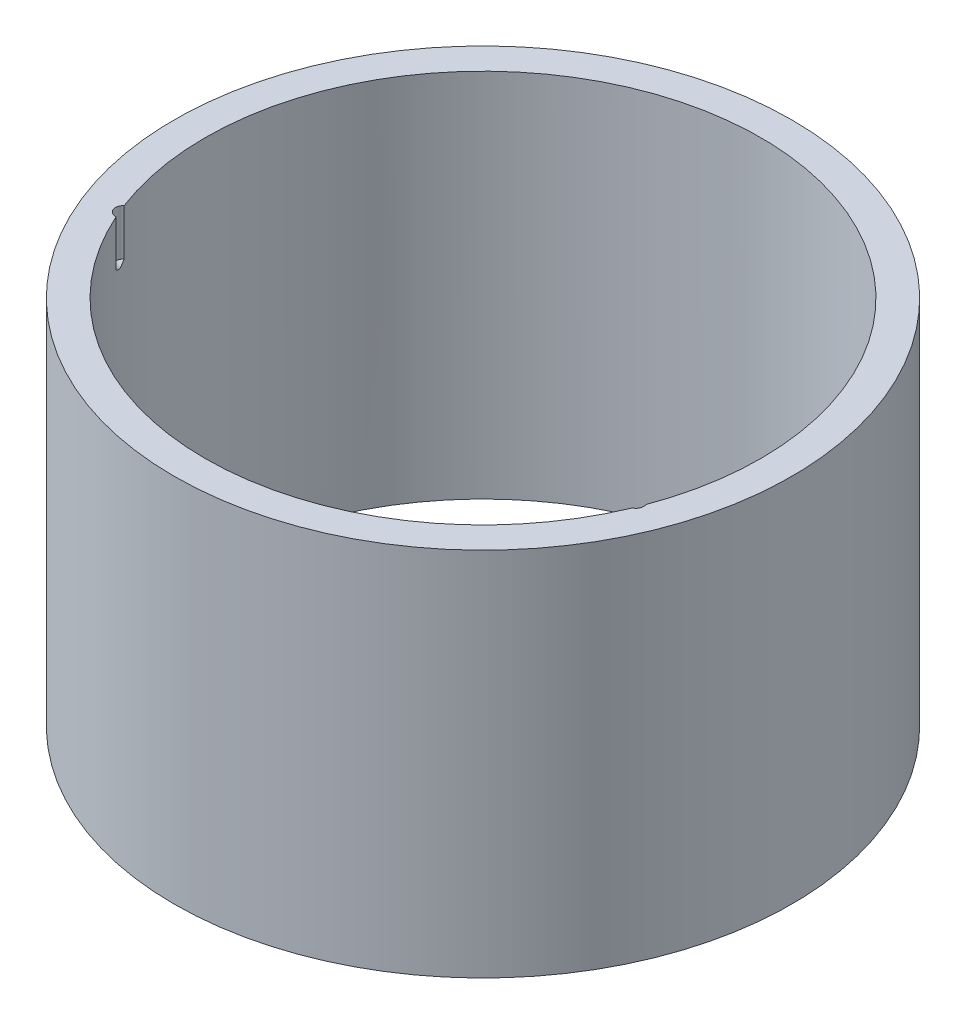
SolidWorks part; units mm, degrees
ref_plane "Front Plane" through (0, 0, 0) normal (0, 0, 1) x (1, 0, 0)
ref_plane "Top Plane" through (0, 0, 0) normal (0, 1, 0) x (1, 0, 0)
ref_plane "Right Plane" through (0, 0, 0) normal (1, 0, 0) x (0, 0, -1)
sketch "Sketch1" plane through (0, 0, 0) normal (0, 1, 0) x (1, 0, 0)
  circle A0 centre (0, 0) radius 50
  dimension "D1" = 100
extrude "Boss-Extrude1" add sketch "Sketch1" along normal blind 60 contours A0
sketch "Sketch2" plane through (0, 60, 0) normal (0, 1, 0) x (1, 0, 0)
  circle A0 centre (0, 0) radius 45
  dimension "D1" = 90
extrude "Cut-Extrude1" cut sketch "Sketch2" against normal through all
hole_wizard "M3 Tapped Hole2" positions "Sketch5" profile "Sketch6" tap size "M3" standard "ISO"
sketch "Sketch5" plane through (-125, 60, -260) normal (0, 1, 0) x (-1, 0, 0)
  point P0 (-125.5887, 346.3435)
  point P1 (-83.7893, 277.0519)
  point P2 (-165.9855, 276.2103)
  point P3 (165.6896, 275.8726)
  point P4 (83.5295, 276.2529)
  point P5 (125.2739, 347.0149)
sketch "Sketch6" plane through (0.5887, 60, 86.3435) normal (1, 0, 0) x (0, 0, 1)
  line L0 (0, 0) -> (0, 8.2511)
  line L1 (0, 8.2511) -> (1.25, 7.5)
  line L2 (1.25, 7.5) -> (1.25, 0)
  line L5 (1.25, 0) -> (0, 0)
  line L10 (0, 8.2511) -> (-1.25, 7.5) construction
  line L11 (0, -6.35) -> (0, 107.95) construction
  dimension "Tap Drill Dia." = 2.5
  dimension "Tap Drill Depth" = 7.5
  dimension "Drill Angle" = 118
